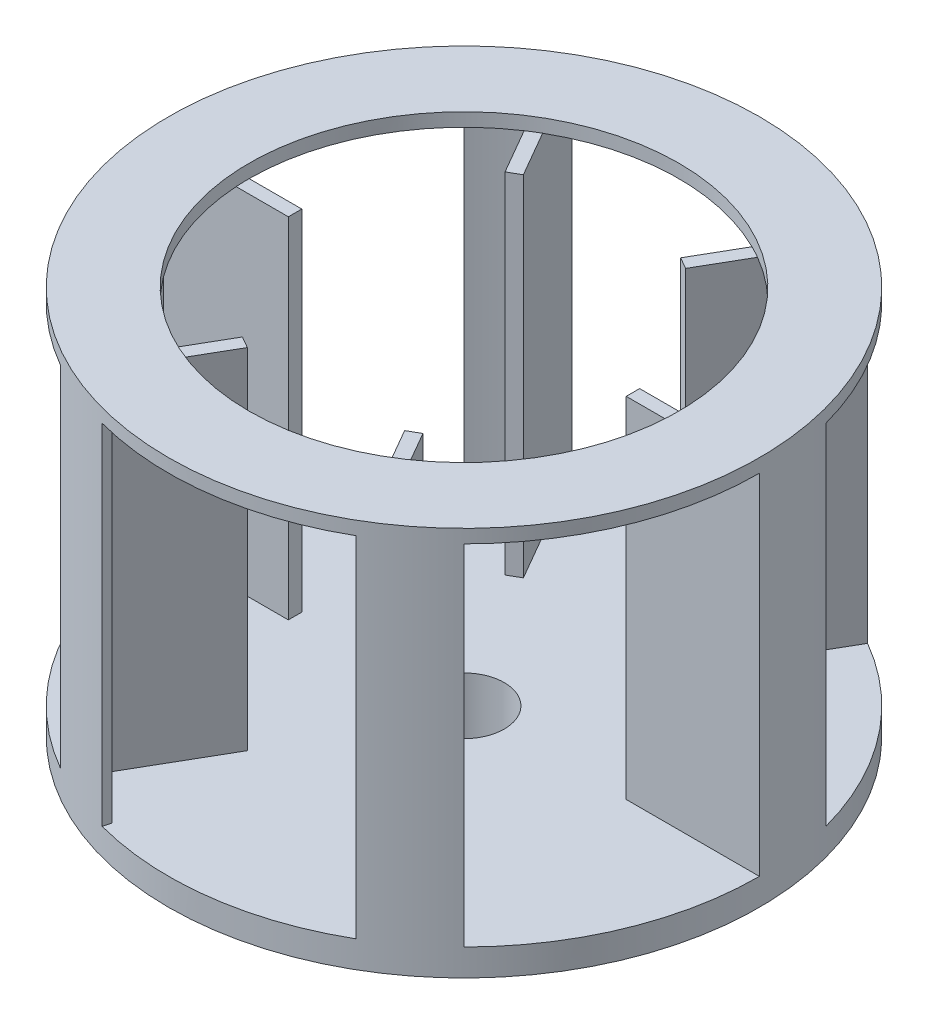
SolidWorks part; units mm, degrees
ref_plane "Front Plane" through (0, 0, 0) normal (0, 0, 1) x (1, 0, 0)
ref_plane "Top Plane" through (0, 0, 0) normal (0, 1, 0) x (1, 0, 0)
ref_plane "Right Plane" through (0, 0, 0) normal (1, 0, 0) x (0, 0, -1)
sketch "Sketch1" plane through (0, 0, 0) normal (0, 1, 0) x (1, 0, 0)
  circle A0 centre (0, 0) radius 137.5
  dimension "D1" = 275
extrude "Boss-Extrude1" add sketch "Sketch1" along normal blind 6.25
sketch "Sketch2" plane through (0, 0, 0) normal (0, -1, 0) x (1, 0, 0)
  line L0 (137.5, 0) -> (75.5, 0)
  line L1 (75.5, 0) -> (75.5, -6.25)
  line L2 (75.5, -6.25) -> (133.6039, -6.25)
  line L3 (129.1926, -34.617) -> (132.8148, -35.5876)
  line L4 (68.75, -119.0785) -> (37.75, -65.3849)
  line L5 (37.75, -65.3849) -> (32.3373, -68.5099)
  line L6 (32.3373, -68.5099) -> (61.3893, -118.8294)
  line L7 (34.617, -129.1926) -> (35.5876, -132.8148)
  line L8 (-68.75, -119.0785) -> (-37.75, -65.3849)
  line L9 (-37.75, -65.3849) -> (-43.1627, -62.2599)
  line L10 (-43.1627, -62.2599) -> (-72.2146, -112.5794)
  line L11 (-94.5755, -94.5755) -> (-97.2272, -97.2272)
  line L12 (-137.5, 0) -> (-75.5, 0)
  line L13 (-75.5, 0) -> (-75.5, 6.25)
  line L14 (-75.5, 6.25) -> (-133.6039, 6.25)
  line L15 (-129.1926, 34.617) -> (-132.8148, 35.5876)
  line L16 (-68.75, 119.0785) -> (-37.75, 65.3849)
  line L17 (-37.75, 65.3849) -> (-32.3373, 68.5099)
  line L18 (-32.3373, 68.5099) -> (-61.3893, 118.8294)
  line L19 (-34.617, 129.1926) -> (-35.5876, 132.8148)
  line L20 (68.75, 119.0785) -> (37.75, 65.3849)
  line L21 (37.75, 65.3849) -> (43.1627, 62.2599)
  line L22 (43.1627, 62.2599) -> (72.2146, 112.5794)
  line L23 (94.5755, 94.5755) -> (97.2272, 97.2272)
  arc A0 (132.8148, -35.5876) -> (137.5, 0) centre (0, 0) ccw
  arc A1 (129.1926, -34.617) -> (133.6039, -6.25) centre (0, 0) ccw
  arc A2 (35.5876, -132.8148) -> (68.75, -119.0785) centre (0, 0) ccw
  arc A3 (34.617, -129.1926) -> (61.3893, -118.8294) centre (0, 0) ccw
  arc A4 (-97.2272, -97.2272) -> (-68.75, -119.0785) centre (0, 0) ccw
  arc A5 (-94.5755, -94.5755) -> (-72.2146, -112.5794) centre (0, 0) ccw
  arc A6 (-132.8148, 35.5876) -> (-137.5, 0) centre (0, 0) ccw
  arc A7 (-129.1926, 34.617) -> (-133.6039, 6.25) centre (0, 0) ccw
  arc A8 (-35.5876, 132.8148) -> (-68.75, 119.0785) centre (0, 0) ccw
  arc A9 (-34.617, 129.1926) -> (-61.3893, 118.8294) centre (0, 0) ccw
  arc A10 (97.2272, 97.2272) -> (68.75, 119.0785) centre (0, 0) ccw
  arc A11 (94.5755, 94.5755) -> (72.2146, 112.5794) centre (0, 0) ccw
  point P41 (0, 0)
  dimension "D4" = 267.5
  dimension "D3" = 275
  dimension "D1" = 62
  dimension "D2" = 6.25
  dimension "D5" = 15
  dimension "D6" = 3.6222
  dimension "D7" = 6
extrude "Boss-Extrude2" add sketch "Sketch2" along normal blind 162.5
sketch "Sketch3" plane through (0, -162.5, 0) normal (0, -1, 0) x (1, 0, 0)
  circle A0 centre (0, 0) radius 137.5
extrude "Boss-Extrude3" add sketch "Sketch3" along normal blind 12.5
sketch "Sketch4" plane through (0, -175, 0) normal (0, -1, 0) x (1, 0, 0)
  circle A0 centre (0, 0) radius 37.5
  dimension "D1" = 75
extrude "Boss-Extrude4" add sketch "Sketch4" along normal blind 62.5
sketch "Sketch5" plane through (0, -237.5, 0) normal (0, -1, 0) x (1, 0, 0)
  circle A0 centre (0, 0) radius 18.75
  dimension "D1" = 37.5
extrude "Cut-Extrude1" cut sketch "Sketch5" against normal up to next and the other way through all
sketch "Sketch6" plane through (0, 6.25, 0) normal (0, 1, 0) x (1, 0, 0)
  circle A0 centre (0, 0) radius 100
  dimension "D1" = 200
extrude "Cut-Extrude2" cut sketch "Sketch6" against normal blind 6.25
